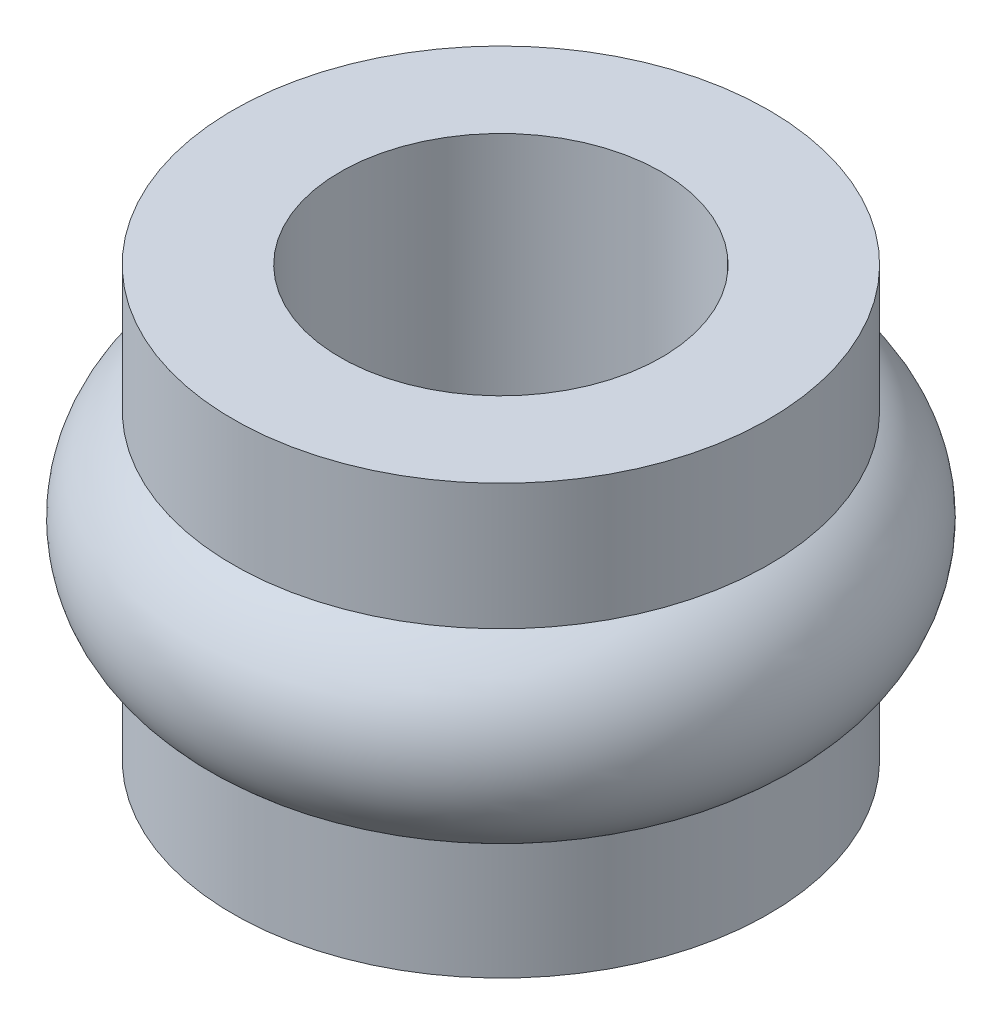
SolidWorks part; units mm, degrees
ref_plane "Front Plane" through (0, 0, 0) normal (0, 0, 1) x (1, 0, 0)
ref_plane "Top Plane" through (0, 0, 0) normal (0, 1, 0) x (1, 0, 0)
ref_plane "Right Plane" through (0, 0, 0) normal (1, 0, 0) x (0, 0, -1)
sketch "Sketch1" plane through (0, 0, 0) normal (0, 0, 1) x (1, 0, 0)
  line L0 (0, 0) -> (0, 1.6143) construction
  line L1 (1.5, 0) -> (1.5, 4)
  line L2 (1.5, 4) -> (2.5, 4)
  line L3 (2.5, 4) -> (2.5, 2.8237)
  line L4 (2.5, 0) -> (1.5, 0)
  line L5 (2, 4) -> (2, -0.0847) construction
  line L6 (2.5, 1.0916) -> (2.5, 0)
  line L7 (2.5, 1.0916) -> (2.5, 2.8237) construction
  line L8 (3, 1.9577) -> (2.5, 1.9577) construction
  arc A1 (2.5, 1.0916) -> (2.5, 2.8237) centre (2, 1.9577) ccw
  dimension "D4" = 0.5
  dimension "D1" = 1.5
  dimension "D2" = 4
  dimension "D3" = 1
revolve "Revolve1" add sketch "Sketch1" angle 360 about L0
